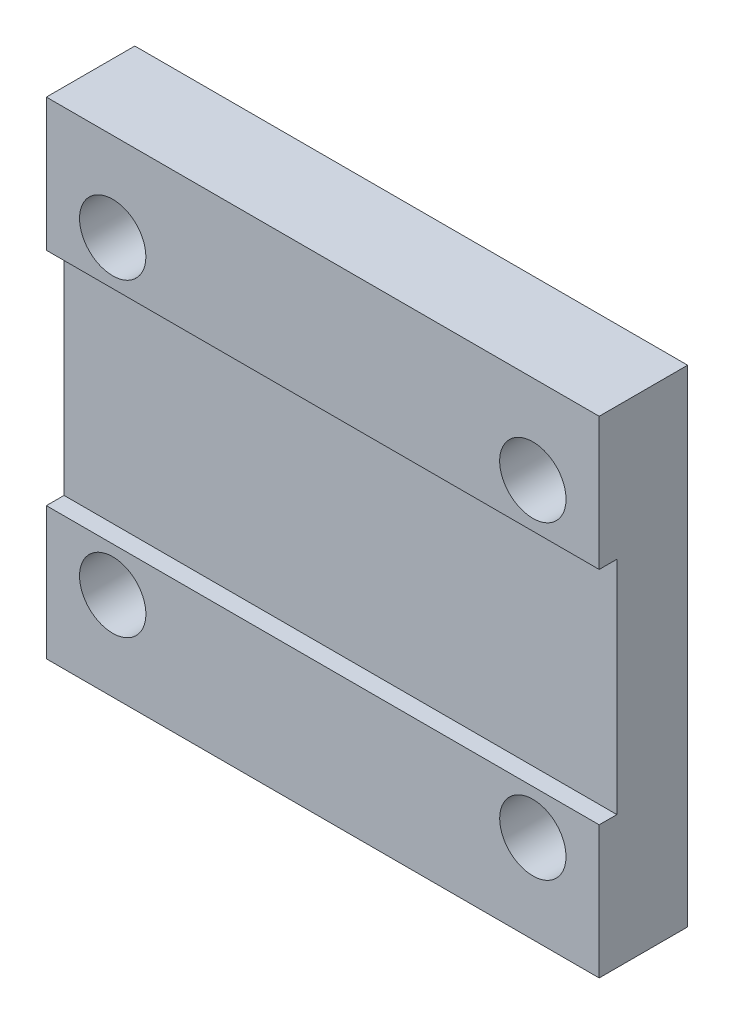
SolidWorks part; units mm, degrees
ref_plane "前视基准面" through (0, 0, 0) normal (0, 0, 1) x (1, 0, 0)
ref_plane "上视基准面" through (0, 0, 0) normal (0, 1, 0) x (1, 0, 0)
ref_plane "右视基准面" through (0, 0, 0) normal (1, 0, 0) x (0, 0, -1)
other "Configuration Table"
sketch "草图1" plane through (0, 0, 0) normal (0, 0, 1) x (1, 0, 0)
  line L0 (-12.5, 7) -> (12.5, 7) construction
  line L1 (-12.5, -11) -> (12.5, -11)
  line L2 (-12.5, -11) -> (-12.5, 11)
  line L3 (-12.5, 11) -> (12.5, 11)
  line L4 (12.5, -11) -> (12.5, 11)
  line L5 (0, 11) -> (0, -11) construction
  line L6 (-12.5, 0) -> (12.5, 0) construction
  circle A0 centre (-9.5, 7) radius 1.5
  circle A1 centre (9.5, 7) radius 1.5
  circle A2 centre (9.5, -7) radius 1.5
  circle A3 centre (-9.5, -7) radius 1.5
  point P0 (0, 0)
  point P10 (0, 0)
  point P11 (0, 0)
  dimension "D4" = 3
  dimension "D1" = 22
  dimension "D2" = 25
  dimension "D3" = 7
  dimension "D5" = 19
  dimension "D6" = 3
extrude "凸台-拉伸1" add sketch "草图1" along normal blind 4
sketch "草图2" plane through (0, 0, 4) normal (0, 0, 1) x (1, 0, 0)
  line L0 (12.5, -11) -> (12.5, 11) construction
  line L1 (-12.5, -5) -> (12.5, -5)
  line L2 (-12.5, -5) -> (-12.5, 5)
  line L3 (-12.5, 5) -> (12.5, 5)
  line L4 (12.5, -5) -> (12.5, 5)
  line L5 (0, 5) -> (0, -5) construction
  line L6 (-12.5, 0) -> (12.5, 0) construction
  point P0 (0, 0)
  dimension "D1" = 10
extrude "切除-拉伸1" cut sketch "草图2" against normal blind 0.8
